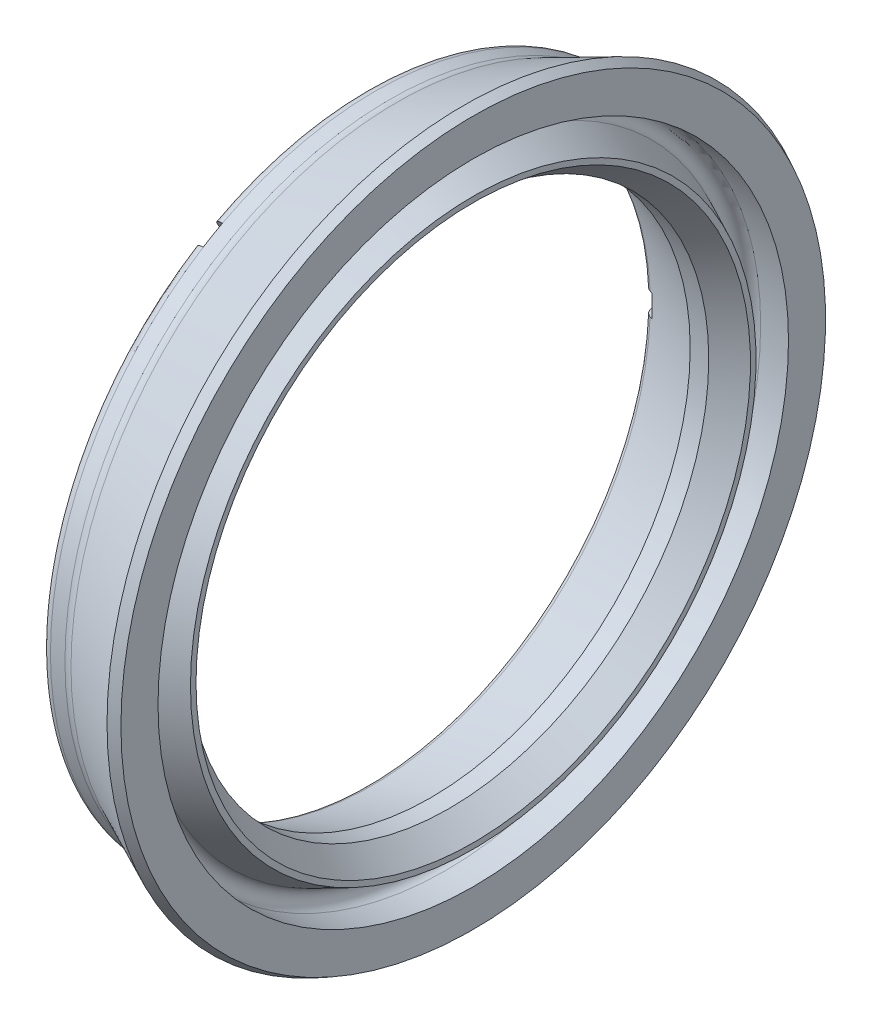
SolidWorks part; units mm, degrees
material "PU93A"
ref_plane "Front Plane" through (0, 0, 0) normal (0, 0, 1) x (1, 0, 0)
ref_plane "Top Plane" through (0, 0, 0) normal (0, 1, 0) x (1, 0, 0)
ref_plane "Right Plane" through (0, 0, 0) normal (1, 0, 0) x (0, 0, -1)
sketch "Sketch1" plane through (0, 0, 0) normal (0, 0, 1) x (1, 0, 0)
  line L0 (0, 0) -> (14.7227, 0) construction
  line L1 (0, 15.4766) -> (0, 17)
  line L2 (0.5, 17.5) -> (1.5, 17.5)
  line L3 (1.5, 17.5) -> (5.3, 19.25)
  line L4 (5.8, 19) -> (5.8, 17)
  line L5 (5.8, 17) -> (4.3, 17)
  line L6 (4.5, 14) -> (3.5, 14)
  line L7 (4.0889, 16.0467) -> (5.8, 15.25)
  line L8 (3.5, 14) -> (0.3488, 15)
  line L9 (5.8, 15.25) -> (5.8, 14.95)
  line L10 (5.8, 14.95) -> (4.5, 14)
  line L12 (5.8, 19) -> (5.3, 19.25)
  arc A0 (4.3, 17) -> (4.0889, 16.0467) centre (4.3, 16.5) ccw
  arc A1 (0.3488, 15) -> (0, 15.4766) centre (0.5, 15.4766) cw
  arc A2 (0, 17) -> (0.5, 17.5) centre (0.5, 17) cw
  dimension "D10" = 35
  dimension "D17" = 0.5
  dimension "D18" = 1
  dimension "D19" = 0.5
  dimension "D4" = 4.5
  dimension "D5" = 38.5
  dimension "D15" = 24.968
  dimension "D2" = 30
  dimension "D3" = 5.8
  dimension "D6" = 30.5
  dimension "D7" = 2
  dimension "D8" = 34
  dimension "D9" = 1.5
  dimension "D11" = 1.8035
  dimension "D12" = 0.5
  dimension "D13" = 28
  dimension "D14" = 33
  dimension "D16" = 1.5
  dimension "D20" = 0.3
revolve "Revolve1" add sketch "Sketch1" angle 360 about L0
fillet "Fillet1" radius 1 1 edges at (1.5, 0, 17.5)
sketch "Sketch2" plane through (0, 0, 0) normal (-1, 0, 0) x (0, 0, 1)
  arc A0 (-15.7873, 0.6342) -> (15.6077, 2.4577) centre (0, 0) cw construction
  text T0 "RLN TSS  28 36 6.3" font "Century Gothic" height 0.8
  dimension "D1" = 15.8
extrude "Cut-Extrude1" cut sketch "Sketch2" against normal blind 0.1
sketch "Sketch3" plane through (0, 0, 0) normal (0, 0, 1) x (1, 0, 0)
  line L1 (-0.5, 0.6) -> (0.5, 0.6)
  line L2 (-0.5, 0.6) -> (-0.5, -0.6)
  line L3 (-0.5, -0.6) -> (0.5, -0.6)
  line L4 (0.5, 0.6) -> (0.5, -0.6)
  line L5 (-0.5, 0.6) -> (0.5, -0.6) construction
  line L6 (-0.5, -0.6) -> (0.5, 0.6) construction
  point P0 (0, 0)
  dimension "D1" = 0.5
  dimension "D2" = 1.2
extrude "Cut-Extrude2" cut sketch "Sketch3" against normal through all contours L3 L4 L1 L2
pattern_circular "CirPattern1" count 3 over 360 about axis through (0, 0, 0) along (1, 0, 0) of "Cut-Extrude2"
